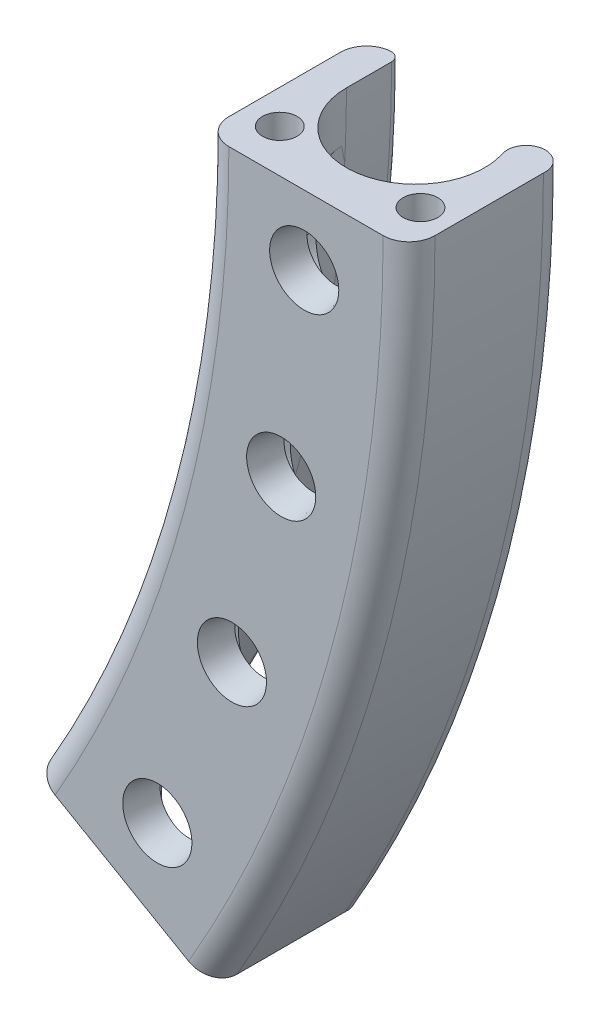
SolidWorks part; units mm, degrees
ref_plane "Front Plane" through (0, 0, 0) normal (0, 0, 1) x (1, 0, 0)
ref_plane "Top Plane" through (0, 0, 0) normal (0, 1, 0) x (1, 0, 0)
ref_plane "Right Plane" through (0, 0, 0) normal (1, 0, 0) x (0, 0, -1)
sketch "Sketch1" plane through (0, 0, 0) normal (0, 0, 1) x (1, 0, 0)
  circle A0 centre (0, 0) radius 159 construction
  dimension "D1" = 318
sketch "Sketch2" plane through (0, 0, 0) normal (0, 1, 0) x (1, 0, 0)
  line L3 (150.0838, -12.6752) -> (167.9253, -12.6752)
  line L4 (151, 0) -> (151, 6.24)
  line L5 (151, 6.24) -> (150.0838, 6.24)
  line L6 (147.0838, 3.24) -> (147.0838, -9.6752)
  line L9 (170.9253, 2.8715) -> (170.9253, -9.6752)
  circle A0 centre (159, 0) radius 8 construction
  arc A1 (151, 0) -> (166.6258, 2.4181) centre (159, 0) ccw
  arc A2 (150.0838, -12.6752) -> (147.0838, -9.6752) centre (150.0838, -9.6752) cw
  arc A3 (167.9253, -12.6752) -> (170.9253, -9.6752) centre (167.9253, -9.6752) ccw
  arc A4 (166.6258, 2.4181) -> (170.9253, 2.8715) centre (168.7291, 3.0851) cw
  arc A5 (150.0838, 6.24) -> (147.0838, 3.24) centre (150.0838, 3.24) ccw
  circle A6 centre (167.2779, -7.7056) radius 2
  circle A7 centre (151, -7.7056) radius 2
  point P21 (151, -7.7056)
  point P22 (167.2779, -7.7056)
  dimension "D1" = 16
  dimension "D2" = 3
  dimension "D3" = 4
sketch "Sketch3" plane through (0, 0, 0) normal (0, 0, 1) x (1, 0, 0)
  line L0 (0, 0) -> (137.698, -79.5) construction
  line L1 (0, 0) -> (159, 0) construction
  arc A0 (159, 0) -> (137.698, -79.5) centre (0, 0) cw
  dimension "D1" = 30
sweep "Sweep1" add profiles "Sketch2" path "Sketch3"
sketch "Sketch4" plane through (0, 0, 12.6752) normal (0, 0, 1) x (1, 0, 0)
  circle A0 centre (158.797, -8.033) radius 4
  circle A1 centre (0, 0) radius 159 construction
  point P2 (0, 0)
  point P6 (158.8662, -6.5212)
  point P7 (158.797, -8.033)
  dimension "D1" = 8
extrude "Cut-Extrude1" cut sketch "Sketch4" against normal blind 10 draft 10
sketch "Sketch5" plane through (0, 0, 0) normal (0, 0, 1) x (1, 0, 0)
  line L0 (158.797, -8.033) -> (0, 0) construction
  line L1 (166.6856, -10.4371) -> (150.706, -9.6288)
  line L2 (166.6856, -10.4371) -> (166.8879, -6.4371)
  line L3 (166.8879, -6.4371) -> (150.9083, -5.6288)
  line L4 (150.706, -9.6288) -> (150.9083, -5.6288)
  line L5 (166.6856, -10.4371) -> (150.9083, -5.6288) construction
  line L6 (166.8879, -6.4371) -> (150.706, -9.6288) construction
  circle A0 centre (158.797, -8.033) radius 5.4235
  circle A1 centre (0, 0) radius 159 construction
  circle A2 centre (158.797, -8.033) radius 4 construction
  dimension "D1" = 16
  dimension "D2" = 4
extrude "Cut-Extrude4" cut sketch "Sketch5" along normal blind 9 contours L1 A0 | L3 A0 | A0 L3 L4 L1 | L3 A0 L1 | A0 L1 L2 L3
pattern_circular "CirPattern1" count 4 every 8 about axis through (0, 0, 0) along (0, 0, 1) of "Cut-Extrude1", "Cut-Extrude4"
fillet "Fillet1" radius 1 1 edges at (145.8548, -39.0817, -6.24)
